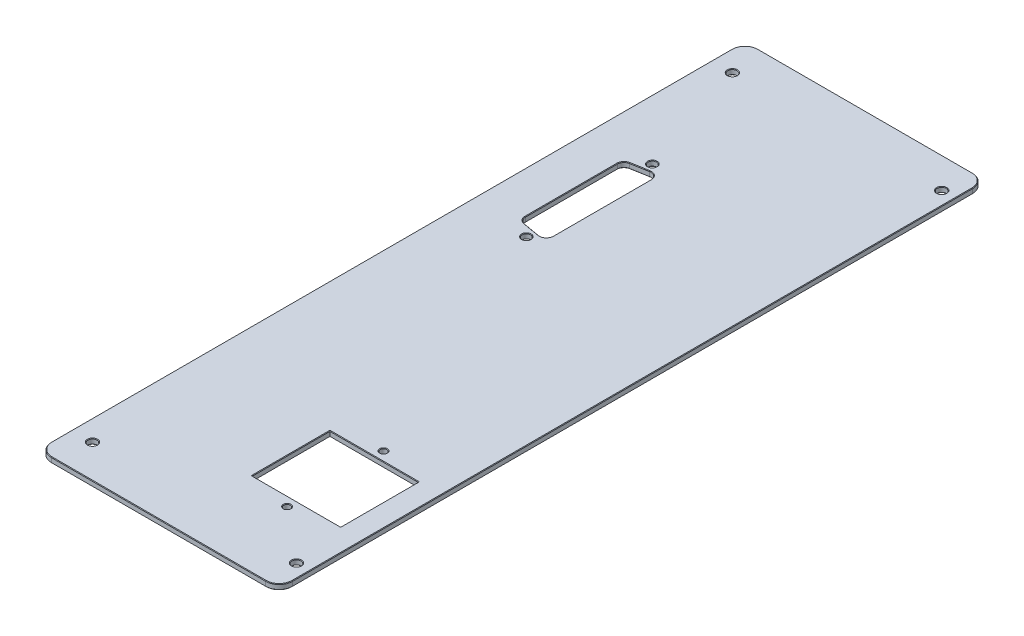
SolidWorks part; units mm, degrees
ref_plane "Plan1" through (0, 0, 0) normal (0, 0, 1) x (1, 0, 0)
ref_plane "Plan2" through (0, 0, 0) normal (0, 1, 0) x (1, 0, 0)
ref_plane "Plan3" through (0, 0, 0) normal (1, 0, 0) x (0, 0, -1)
sketch "Esquisse1" plane through (0, 0, 0) normal (0, 0, 1) x (1, 0, 0)
  line L0 (0, 0) -> (90, 0)
  line L1 (0, 0) -> (0, 2)
  line L2 (90, 2) -> (0, 2)
  line L3 (90, 2) -> (90, 0)
  dimension "D1" = 90
  dimension "D2" = 2
extrude "Base-Extrusion" add sketch "Esquisse1" along normal blind 264
sketch "Esquisse2" plane through (0, 2, 0) normal (0, 1, 0) x (-1, 0, 0)
  line L0 (-81.5, 232.5) -> (-48.5, 232.5)
  line L1 (-81.5, 232.5) -> (-81.5, 203.5)
  line L2 (-48.5, 203.5) -> (-81.5, 203.5)
  line L3 (-48.5, 203.5) -> (-48.5, 232.5)
  line L4 (-90, 0) -> (0, 0) construction
  line L5 (0, 264) -> (0, 0) construction
  dimension "D1" = 33
  dimension "D2" = 29
  dimension "D3" = 203.5
  dimension "D4" = 48.5
extrude "Enlèv. mat.-Extru.1" cut sketch "Esquisse2" against normal through all
sketch "Esquisse3" plane through (0, 2, 0) normal (0, 1, 0) x (-1, 0, 0)
  line L0 (-27.1, 98.7706) -> (-27.1, 62.2294)
  line L1 (-24.1659, 59.7674) -> (-17.7659, 60.8959)
  line L2 (-15.7, 63.3579) -> (-15.7, 97.6421)
  line L3 (-17.7659, 100.1041) -> (-24.1659, 101.2326)
  line L4 (-53.1345, 80.5) -> (-7.943, 80.5) construction
  line L5 (-22.4, 119.1204) -> (-22.4, 48.6218) construction
  line L6 (-90, 0) -> (0, 0) construction
  line L7 (0, 264) -> (0, 0) construction
  arc A0 (-24.1659, 59.7674) -> (-27.1, 62.2294) centre (-24.6, 62.2294) cw
  arc A1 (-15.7, 63.3579) -> (-17.7659, 60.8959) centre (-18.2, 63.3579) cw
  arc A2 (-17.7659, 100.1041) -> (-15.7, 97.6421) centre (-18.2, 97.6421) cw
  arc A3 (-24.1659, 101.2326) -> (-27.1, 98.7706) centre (-24.6, 98.7706) ccw
  point P14 (-27.1, 59.25)
  point P21 (-27.1, 101.75)
  dimension "D6" = 2.5
  dimension "D1" = 80.5
  dimension "D2" = 22.4
  dimension "D3" = 21.25
  dimension "D4" = 42.5
  dimension "D5" = 11.4
  dimension "D7" = 80
  dimension "D8" = 6.7
extrude "Enlèv. mat.-Extru.2" cut sketch "Esquisse3" against normal through all
sketch "Esquisse4" plane through (0, 2, 0) normal (0, 1, 0) x (-1, 0, 0)
  line L0 (-7.82, 271.8674) -> (-7.82, -8.3193) construction
  line L1 (-85, 271.8674) -> (-85, -15.55) construction
  line L2 (-22.4, 154.3697) -> (-22.4, 45.4585) construction
  line L3 (-65, 255.5985) -> (-65, 185.5518) construction
  line L4 (0, 264) -> (0, 0) construction
  line L5 (-90, 264) -> (-90, 0) construction
  line L6 (-90, 0) -> (0, 0) construction
  circle A0 centre (-22.4, 104.02) radius 1.6
  circle A1 centre (-22.4, 56.98) radius 1.6
  circle A2 centre (-85, 252.5) radius 1.7
  circle A3 centre (-85, 11.5) radius 1.7
  circle A4 centre (-7.82, 12.49) radius 1.7
  circle A5 centre (-7.82, 251.51) radius 1.7
  circle A6 centre (-65, 236) radius 1.25
  circle A7 centre (-65, 200) radius 1.25
  dimension "D5" = 2.5
  dimension "D6" = 36
  dimension "D7" = 3.2
  dimension "D8" = 47.04
  dimension "D9" = 3.4
  dimension "D10" = 241
  dimension "D12" = 12.49
  dimension "D13" = 11.5
  dimension "D14" = 56.98
  dimension "D15" = 200
  dimension "D1" = 22.4
  dimension "D2" = 7.82
  dimension "D3" = 5
  dimension "D4" = 65
  dimension "D11" = 239.02
extrude "Enlèv. mat.-Extru.3" cut sketch "Esquisse4" against normal through all
fillet "Congé1" radius 5
chamfer "Chanfrein1" distance 0.2 angle 45
